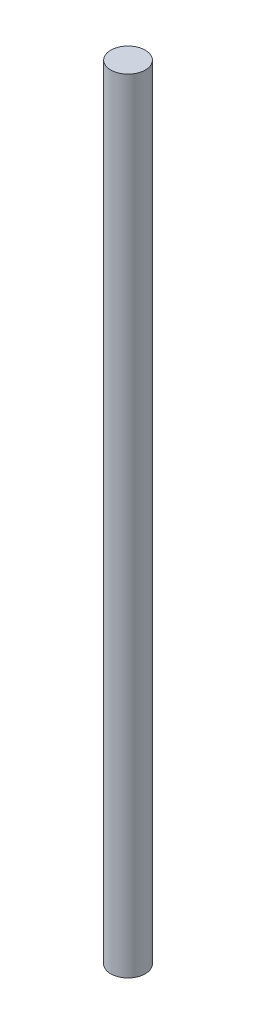
SolidWorks part; units mm, degrees
material "Nylon 101"
ref_plane "Alzado" through (0, 0, 0) normal (0, 0, 1) x (1, 0, 0)
ref_plane "Planta" through (0, 0, 0) normal (0, 1, 0) x (1, 0, 0)
ref_plane "Vista lateral" through (0, 0, 0) normal (1, 0, 0) x (0, 0, -1)
sketch "Sketch1" plane through (0, 0, 0) normal (0, 0, 1) x (1, 0, 0)
  line L0 (0, 0) -> (1.3, 0)
  line L1 (1.3, 0) -> (1.3, -59)
  line L2 (1.3, -59) -> (0, -59)
  line L3 (0, -59) -> (0, 0)
  line L4 (0, -63) -> (0, 4) construction
revolve "Tendon" add sketch "Sketch1" angle 360 about L4
